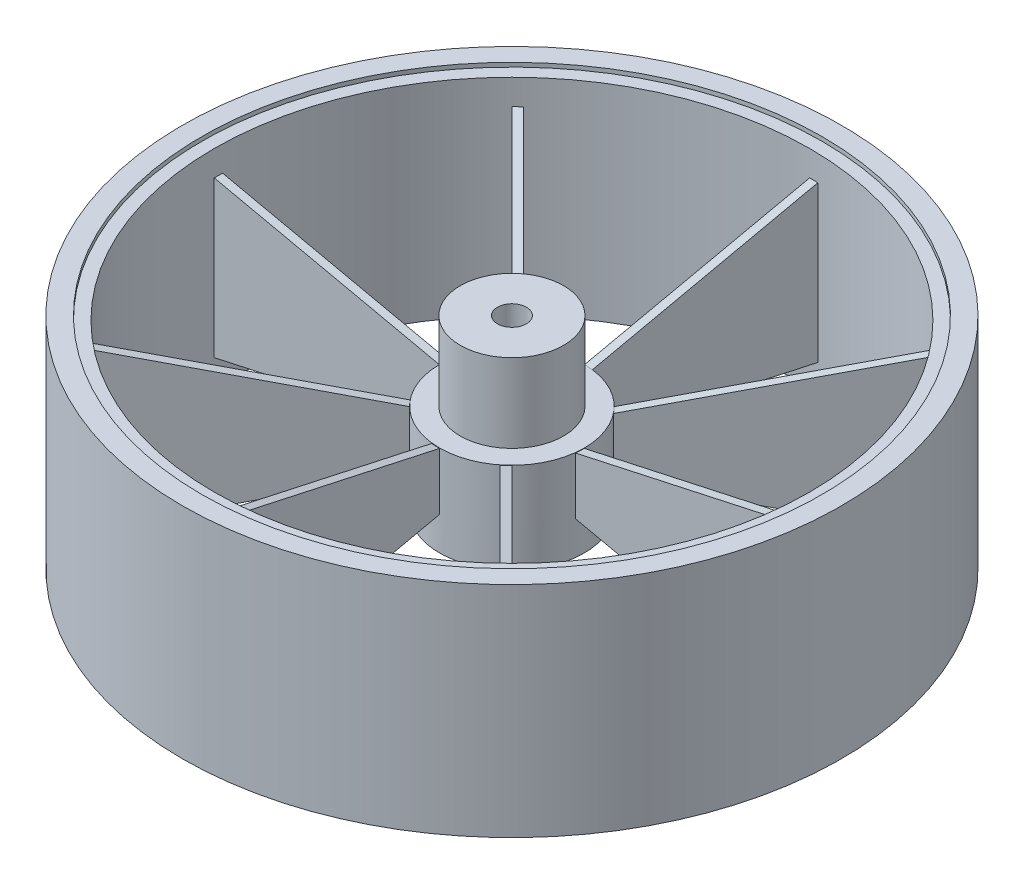
SolidWorks part; units mm, degrees
ref_plane "Front Plane" through (0, 0, 0) normal (0, 0, 1) x (1, 0, 0)
ref_plane "Top Plane" through (0, 0, 0) normal (0, 1, 0) x (1, 0, 0)
ref_plane "Right Plane" through (0, 0, 0) normal (1, 0, 0) x (0, 0, -1)
sketch "Sketch1" plane through (0, 0, 0) normal (0, 1, 0) x (1, 0, 0)
  circle A0 centre (0, 0) radius 75
  circle A1 centre (0, 0) radius 72
  circle A2 centre (0, 0) radius 17.5
  dimension "D1" = 144
  dimension "D2" = 150
  dimension "D3" = 35
extrude "Boss-Extrude1" add sketch "Sketch1" along normal blind 50 contours A2 | A0 A1
sketch "Sketch2" plane through (0, 0, 0) normal (0, -1, 0) x (1, 0, 0)
  circle A0 centre (0, 0) radius 17.5
extrude "Cut-Extrude1" cut sketch "Sketch2" against normal blind 10
ref_plane "Plane1" through (0, 25, 0) normal (0, 1, 0) x (1, 0, 0)
mirror "Mirror1" about plane through (0, 25, 0) normal (0, 1, 0) of "Cut-Extrude1"
sketch "Sketch3" plane through (0, 0, 0) normal (1, 0, 0) x (0, 0, -1)
  line L0 (16.7185, 18.2538) -> (16.7185, 31.7497)
  line L2 (16.7185, 31.7497) -> (73.7455, 44.207)
  line L3 (73.7455, 44.207) -> (73.7455, 5.7965)
  line L4 (73.7455, 5.7965) -> (16.7185, 18.2538)
extrude "Boss-Extrude2" add sketch "Sketch3" along normal blind 2
pattern_circular "CirPattern1" count 8 over 360 about axis through (0, 0, 0) along (0, 1, 0) of "Boss-Extrude2"
sketch "Sketch4" plane through (0, 40, 0) normal (0, 1, 0) x (1, 0, 0)
  circle A0 centre (0, 0) radius 17.5
extrude "Cut-Extrude2" cut sketch "Sketch4" against normal blind 8
sketch "Sketch6" plane through (0, 32, 0) normal (0, 1, 0) x (1, 0, 0)
  circle A0 centre (0, 0) radius 12.5
  dimension "D1" = 25
extrude "Boss-Extrude3" add sketch "Sketch6" along normal blind 19
sketch "Sketch7" plane through (0, 51, 0) normal (0, 1, 0) x (1, 0, 0)
  circle A0 centre (0, 0) radius 3.5
  dimension "D1" = 7
extrude "Cut-Extrude3" cut sketch "Sketch7" against normal blind 42
sketch "Sketch8" plane through (0, 0, 0) normal (1, 0, 0) x (0, 0, -1)
  circle A0 centre (0, 41.7379) radius 2
  dimension "D1" = 4
extrude "Cut-Extrude4" cut sketch "Sketch8" against normal blind 18 and the other way blind 3
sketch "Sketch9" plane through (0, 0, 0) normal (0, 1, 0) x (1, 0, 0)
  circle A0 centre (0, 0) radius 75
  circle A1 centre (0, 0) radius 79.7106
extrude "Boss-Extrude4" add sketch "Sketch9" along normal blind 51 and the other way blind 2
